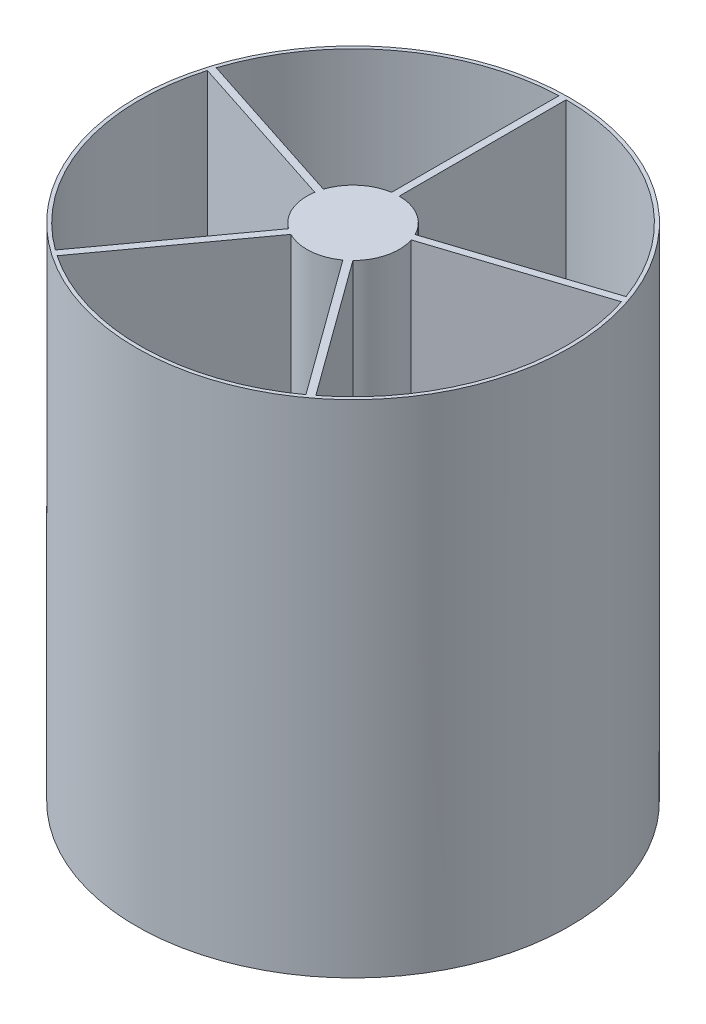
SolidWorks part; units mm, degrees
ref_plane "Front Plane" through (0, 0, 0) normal (0, 0, 1) x (1, 0, 0)
ref_plane "Top Plane" through (0, 0, 0) normal (0, 1, 0) x (1, 0, 0)
ref_plane "Right Plane" through (0, 0, 0) normal (1, 0, 0) x (0, 0, -1)
sketch "Sketch3" plane through (0, 0, 0) normal (0, 1, 0) x (1, 0, 0)
  line L0 (0, 65) -> (0, 300)
  line L1 (61.8187, 20.0861) -> (285.317, 92.7051)
  line L2 (38.206, -52.5861) -> (176.3356, -242.7051)
  line L3 (-38.206, -52.5861) -> (-176.3356, -242.7051)
  line L4 (-61.8187, 20.0861) -> (-285.317, 92.7051)
  line L5 (-10, 299.8333) -> (-10, 64.2262)
  line L6 (282.0682, 102.1641) -> (57.9925, 29.3575)
  line L7 (184.3278, -236.6924) -> (45.8414, -46.0822)
  line L8 (-168.1474, -248.4481) -> (-29.661, -57.8379)
  line L9 (-288.2486, 83.143) -> (-64.1729, 10.3364)
  circle A0 centre (0, 0) radius 60
  circle A1 centre (0, 0) radius 65
  circle A2 centre (0, 0) radius 305
  circle A3 centre (0, 0) radius 300
  dimension "D1" = 120
  dimension "D2" = 130
  dimension "D3" = 600
  dimension "D4" = 610
  dimension "D6" = 10
  dimension "D7" = 5
  dimension "D5" = 5
extrude "Boss-Extrude1" add sketch "Sketch3" along normal blind 700 contours L2 A3 L7 A1 | A2 A3 | L1 A3 L6 A1 | L3 A3 L8 A1 | A1 A0 | L4 A3 L9 A1 | L0 A3 L5 A1
sketch "Sketch4" plane through (0, 0, 0) normal (0, -1, 0) x (1, 0, 0)
  circle A0 centre (0, 0) radius 305
extrude "Boss-Extrude2" add sketch "Sketch4" along normal blind 5
sketch "Sketch5" plane through (0, 700, 0) normal (0, 1, 0) x (1, 0, 0)
  circle A0 centre (0, 0) radius 60
extrude "Boss-Extrude3" add sketch "Sketch5" against normal blind 5
